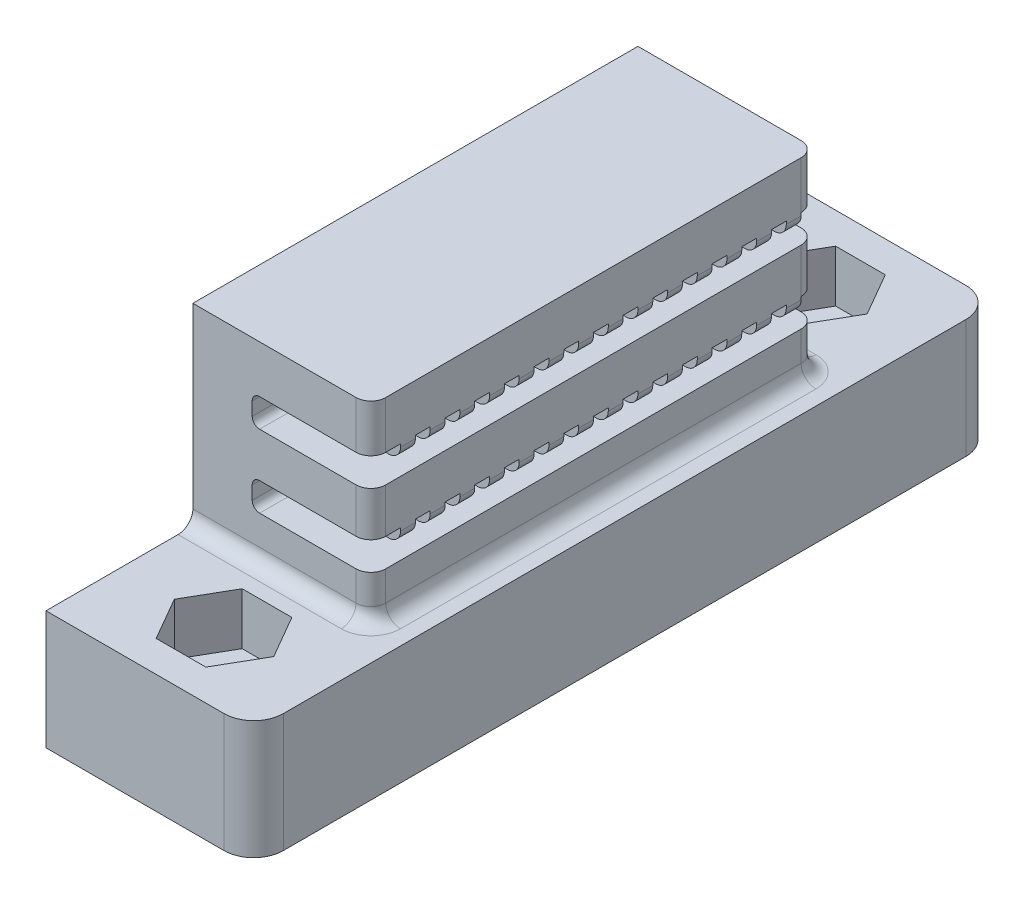
SolidWorks part; units mm, degrees
ref_plane "Alzado" through (0, 0, 0) normal (0, 0, 1) x (1, 0, 0)
ref_plane "Planta" through (0, 0, 0) normal (0, 1, 0) x (1, 0, 0)
ref_plane "Vista lateral" through (0, 0, 0) normal (1, 0, 0) x (0, 0, -1)
sketch "Croquis1" plane through (0, 0, 0) normal (0, 1, 0) x (1, 0, 0)
  line L0 (0, 25) -> (14, 25) construction
  line L1 (0, 0) -> (14, 0)
  line L2 (0, 0) -> (0, 50)
  line L3 (0, 50) -> (14, 50)
  line L4 (14, 0) -> (14, 50)
  line L5 (7, 50) -> (7, 0) construction
  circle A0 centre (7, 45) radius 1.55
  circle A1 centre (7, 5) radius 1.55
  dimension "D3" = 3.1
  dimension "D1" = 50
  dimension "D2" = 14
  dimension "D4" = 20
extrude "Saliente-Extruir1" add sketch "Croquis1" along normal blind 8
sketch "Croquis2" plane through (0, 8, 0) normal (0, 1, 0) x (1, 0, 0)
  line L1 (10.3486, 45) -> (8.6743, 47.9)
  line L2 (8.6743, 47.9) -> (5.3257, 47.9)
  line L3 (5.3257, 47.9) -> (3.6514, 45)
  line L4 (3.6514, 45) -> (5.3257, 42.1)
  line L5 (5.3257, 42.1) -> (8.6743, 42.1)
  line L6 (8.6743, 42.1) -> (10.3486, 45)
  line L7 (10.3486, 5) -> (8.6743, 7.9)
  line L8 (8.6743, 7.9) -> (5.3257, 7.9)
  line L9 (5.3257, 7.9) -> (3.6514, 5)
  line L10 (3.6514, 5) -> (5.3257, 2.1)
  line L11 (5.3257, 2.1) -> (8.6743, 2.1)
  line L12 (8.6743, 2.1) -> (10.3486, 5)
  circle A2 centre (7, 45) radius 2.9 construction
  circle A3 centre (7, 5) radius 2.9 construction
  dimension "D1" = 5.8
  dimension "D2" = 5.8
extrude "Cortar-Extruir1" cut sketch "Croquis2" against normal blind 3.5
sketch "Croquis3" plane through (0, 8, 0) normal (0, 1, 0) x (1, 0, 0)
  line L0 (0, 50) -> (0, 0) construction
  line L1 (0, 39.9) -> (14, 39.9)
  line L2 (0, 39.9) -> (0, 9.9)
  line L3 (0, 9.9) -> (14, 9.9)
  line L4 (14, 39.9) -> (14, 9.9)
  line L5 (14, 0) -> (14, 50) construction
  line L6 (5.3257, 42.1) -> (8.6743, 42.1) construction
  dimension "D1" = 30
  dimension "D2" = 2.2
extrude "Saliente-Extruir3" add sketch "Croquis3" along normal blind 13
sketch "Croquis4" plane through (14, 0, 0) normal (1, 0, 0) x (0, 0, -1)
  line L0 (39.9, 21) -> (39.9, 8) construction
  line L1 (39.9, 17.8) -> (38.9, 17.8)
  line L2 (39.9, 17.8) -> (39.9, 15.9)
  line L3 (39.9, 15.9) -> (9.9, 15.9)
  line L4 (9.9, 17.8) -> (9.9, 15.9)
  line L5 (9.9, 21) -> (9.9, 8) construction
  line L6 (39.9, 8) -> (50, 8) construction
  line L7 (39.9, 12.9) -> (38.9, 12.9)
  line L8 (39.9, 12.9) -> (39.9, 11)
  line L9 (39.9, 11) -> (9.9, 11)
  line L10 (9.9, 12.9) -> (9.9, 11)
  line L11 (36.9, 17.8) -> (36.9, 16.8)
  line L13 (38.9, 17.8) -> (38.9, 16.8)
  line L14 (38.9, 16.8) -> (37.9, 16.8)
  line L15 (37.9, 17.8) -> (37.9, 16.8)
  line L16 (36.9, 16.8) -> (35.9, 16.8)
  line L17 (35.9, 17.8) -> (35.9, 16.8)
  line L18 (34.9, 17.8) -> (34.9, 16.8)
  line L19 (34.9, 16.8) -> (33.9, 16.8)
  line L20 (33.9, 17.8) -> (33.9, 16.8)
  line L21 (32.9, 17.8) -> (32.9, 16.8)
  line L22 (32.9, 16.8) -> (31.9, 16.8)
  line L23 (31.9, 17.8) -> (31.9, 16.8)
  line L24 (30.9, 17.8) -> (30.9, 16.8)
  line L25 (30.9, 16.8) -> (29.9, 16.8)
  line L26 (29.9, 17.8) -> (29.9, 16.8)
  line L27 (28.9, 17.8) -> (28.9, 16.8)
  line L28 (28.9, 16.8) -> (27.9, 16.8)
  line L29 (27.9, 17.8) -> (27.9, 16.8)
  line L30 (26.9, 17.8) -> (26.9, 16.8)
  line L31 (26.9, 16.8) -> (25.9, 16.8)
  line L32 (25.9, 17.8) -> (25.9, 16.8)
  line L33 (24.9, 17.8) -> (24.9, 16.8)
  line L34 (24.9, 16.8) -> (23.9, 16.8)
  line L35 (23.9, 17.8) -> (23.9, 16.8)
  line L36 (22.9, 17.8) -> (22.9, 16.8)
  line L37 (22.9, 16.8) -> (21.9, 16.8)
  line L38 (21.9, 17.8) -> (21.9, 16.8)
  line L39 (20.9, 17.8) -> (20.9, 16.8)
  line L40 (20.9, 16.8) -> (19.9, 16.8)
  line L41 (19.9, 17.8) -> (19.9, 16.8)
  line L42 (18.9, 17.8) -> (18.9, 16.8)
  line L43 (18.9, 16.8) -> (17.9, 16.8)
  line L44 (17.9, 17.8) -> (17.9, 16.8)
  line L45 (16.9, 17.8) -> (16.9, 16.8)
  line L46 (16.9, 16.8) -> (15.9, 16.8)
  line L47 (15.9, 17.8) -> (15.9, 16.8)
  line L48 (14.9, 17.8) -> (14.9, 16.8)
  line L49 (14.9, 16.8) -> (13.9, 16.8)
  line L50 (13.9, 17.8) -> (13.9, 16.8)
  line L51 (12.9, 17.8) -> (12.9, 16.8)
  line L52 (12.9, 16.8) -> (11.9, 16.8)
  line L53 (11.9, 17.8) -> (11.9, 16.8)
  line L54 (38.9, 17.8) -> (36.9, 17.8) construction
  line L55 (36.9, 12.9) -> (36.9, 11.9)
  line L57 (38.9, 12.9) -> (38.9, 11.9)
  line L58 (38.9, 11.9) -> (37.9, 11.9)
  line L59 (37.9, 12.9) -> (37.9, 11.9)
  line L60 (36.9, 11.9) -> (35.9, 11.9)
  line L61 (35.9, 12.9) -> (35.9, 11.9)
  line L62 (34.9, 12.9) -> (34.9, 11.9)
  line L63 (34.9, 11.9) -> (33.9, 11.9)
  line L64 (33.9, 12.9) -> (33.9, 11.9)
  line L65 (32.9, 12.9) -> (32.9, 11.9)
  line L66 (32.9, 11.9) -> (31.9, 11.9)
  line L67 (31.9, 12.9) -> (31.9, 11.9)
  line L68 (30.9, 12.9) -> (30.9, 11.9)
  line L69 (30.9, 11.9) -> (29.9, 11.9)
  line L70 (29.9, 12.9) -> (29.9, 11.9)
  line L71 (28.9, 12.9) -> (28.9, 11.9)
  line L72 (28.9, 11.9) -> (27.9, 11.9)
  line L73 (27.9, 12.9) -> (27.9, 11.9)
  line L74 (26.9, 12.9) -> (26.9, 11.9)
  line L75 (26.9, 11.9) -> (25.9, 11.9)
  line L76 (25.9, 12.9) -> (25.9, 11.9)
  line L77 (24.9, 12.9) -> (24.9, 11.9)
  line L78 (24.9, 11.9) -> (23.9, 11.9)
  line L79 (23.9, 12.9) -> (23.9, 11.9)
  line L80 (22.9, 12.9) -> (22.9, 11.9)
  line L81 (22.9, 11.9) -> (21.9, 11.9)
  line L82 (21.9, 12.9) -> (21.9, 11.9)
  line L83 (20.9, 12.9) -> (20.9, 11.9)
  line L84 (20.9, 11.9) -> (19.9, 11.9)
  line L85 (19.9, 12.9) -> (19.9, 11.9)
  line L86 (18.9, 12.9) -> (18.9, 11.9)
  line L87 (18.9, 11.9) -> (17.9, 11.9)
  line L88 (17.9, 12.9) -> (17.9, 11.9)
  line L89 (16.9, 12.9) -> (16.9, 11.9)
  line L90 (16.9, 11.9) -> (15.9, 11.9)
  line L91 (15.9, 12.9) -> (15.9, 11.9)
  line L92 (14.9, 12.9) -> (14.9, 11.9)
  line L93 (14.9, 11.9) -> (13.9, 11.9)
  line L94 (13.9, 12.9) -> (13.9, 11.9)
  line L95 (12.9, 12.9) -> (12.9, 11.9)
  line L96 (12.9, 11.9) -> (11.9, 11.9)
  line L97 (11.9, 12.9) -> (11.9, 11.9)
  line L98 (38.9, 12.9) -> (36.9, 12.9) construction
  line L99 (37.9, 17.8) -> (36.9, 17.8)
  line L100 (35.9, 17.8) -> (34.9, 17.8)
  line L101 (33.9, 17.8) -> (32.9, 17.8)
  line L102 (31.9, 17.8) -> (30.9, 17.8)
  line L103 (29.9, 17.8) -> (28.9, 17.8)
  line L104 (27.9, 17.8) -> (26.9, 17.8)
  line L105 (25.9, 17.8) -> (24.9, 17.8)
  line L106 (23.9, 17.8) -> (22.9, 17.8)
  line L107 (21.9, 17.8) -> (20.9, 17.8)
  line L108 (19.9, 17.8) -> (18.9, 17.8)
  line L109 (17.9, 17.8) -> (16.9, 17.8)
  line L110 (15.9, 17.8) -> (14.9, 17.8)
  line L111 (13.9, 17.8) -> (12.9, 17.8)
  line L112 (11.9, 17.8) -> (9.9, 17.8)
  line L113 (37.9, 12.9) -> (36.9, 12.9)
  line L114 (35.9, 12.9) -> (34.9, 12.9)
  line L115 (33.9, 12.9) -> (32.9, 12.9)
  line L116 (31.9, 12.9) -> (30.9, 12.9)
  line L117 (29.9, 12.9) -> (28.9, 12.9)
  line L118 (27.9, 12.9) -> (26.9, 12.9)
  line L119 (25.9, 12.9) -> (24.9, 12.9)
  line L120 (23.9, 12.9) -> (22.9, 12.9)
  line L121 (21.9, 12.9) -> (20.9, 12.9)
  line L122 (19.9, 12.9) -> (18.9, 12.9)
  line L123 (17.9, 12.9) -> (16.9, 12.9)
  line L124 (15.9, 12.9) -> (14.9, 12.9)
  line L125 (13.9, 12.9) -> (12.9, 12.9)
  line L126 (11.9, 12.9) -> (9.9, 12.9)
  dimension "D1" = 1.9
  dimension "D2" = 1.9
  dimension "D3" = 3
  dimension "D4" = 3
  dimension "D5" = 1
  dimension "D6" = 1
  dimension "D7" = 1
  dimension "D9" = 2
  dimension "D10" = 1
  dimension "D11" = 1
  dimension "D12" = 1
  dimension "D14" = 2
  dimension "D8" = 14
  dimension "D13" = 14
extrude "Cortar-Extruir2" cut sketch "Croquis4" against normal blind 10
sketch "Croquis5" plane through (14, 0, 0) normal (1, 0, 0) x (0, 0, -1)
  line L1 (39.9, 8) -> (9.9, 8)
  line L2 (39.9, 8) -> (39.9, 21)
  line L3 (39.9, 21) -> (9.9, 21)
  line L4 (9.9, 8) -> (9.9, 21)
extrude "Cortar-Extruir3" cut sketch "Croquis5" against normal blind 2
fillet "Redondeo1" radius 0.8 28 edges at (12, 11.9, -12.4) (12, 11.9, -14.4) (12, 11.9, -16.4) (12, 11.9, -18.4) (12, 11.9, -20.4) (12, 11.9, -22.4) (12, 11.9, -24.4) (12, 11.9, -26.4) (12, 11.9, -28.4) (12, 11.9, -30.4) (12, 11.9, -32.4) (12, 11.9, -34.4) (12, 11.9, -36.4) (12, 11.9, -38.4) (12, 16.8, -38.4) (12, 16.8, -36.4) (12, 16.8, -34.4) (12, 16.8, -32.4) (12, 16.8, -30.4) (12, 16.8, -28.4) (12, 16.8, -26.4) (12, 16.8, -24.4) (12, 16.8, -22.4) (12, 16.8, -20.4) (12, 16.8, -18.4) (12, 16.8, -16.4) (12, 16.8, -14.4) (12, 16.8, -12.4)
fillet "Redondeo2" radius 2 2 edges at (14, 4, -50) (14, 4, 0)
fillet "Redondeo3" radius 1 6 edges at (12, 19.4, -39.9) (12, 14.4, -39.9) (12, 9.5, -39.9) (12, 9.5, -9.9) (12, 14.4, -9.9) (12, 19.4, -9.9)
fillet "Redondeo4" radius 1 5 edges at (5.5, 8, -9.9) (11.7071, 8, -10.1929) (12, 8, -24.9) (11.7071, 8, -39.6071) (5.5, 8, -39.9)
fillet "Redondeo5" radius 0.5 32 edges at (4, 12.9, -10.9) (4, 12.9, -13.4) (4, 12.9, -15.4) (4, 12.9, -17.4) (4, 12.9, -19.4) (4, 12.9, -21.4) (4, 12.9, -25.4) (4, 12.9, -23.4) (4, 12.9, -27.4) (4, 12.9, -29.4) (4, 12.9, -31.4) (4, 12.9, -33.4) (4, 12.9, -35.4) (4, 12.9, -37.4) (4, 12.9, -39.4) (4, 17.8, -39.4) (4, 17.8, -37.4) (4, 17.8, -35.4) (4, 17.8, -33.4) (4, 17.8, -31.4) (4, 17.8, -29.4) (4, 17.8, -27.4) (4, 17.8, -25.4) (4, 17.8, -23.4) (4, 17.8, -21.4) (4, 17.8, -19.4) (4, 17.8, -17.4) (4, 17.8, -15.4) (4, 17.8, -13.4) (4, 17.8, -10.9) (4, 15.9, -24.9) (4, 11, -24.9)
